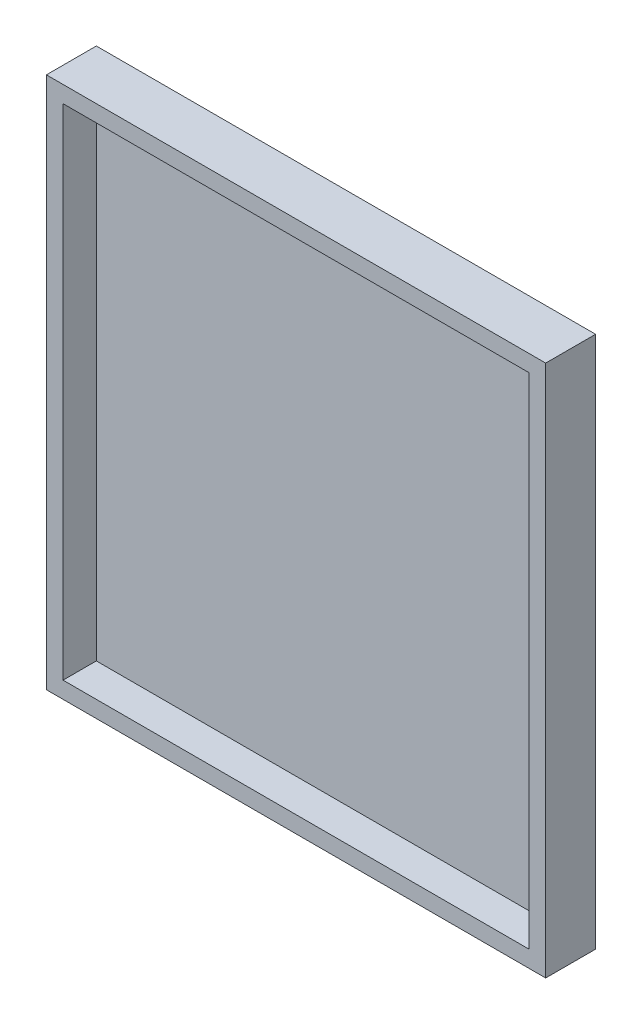
SolidWorks part; units mm, degrees
ref_plane "Front Plane" through (0, 0, 0) normal (0, 0, 1) x (1, 0, 0)
ref_plane "Top Plane" through (0, 0, 0) normal (0, 1, 0) x (1, 0, 0)
ref_plane "Right Plane" through (0, 0, 0) normal (1, 0, 0) x (0, 0, -1)
sketch "Sketch1" plane through (0, 0, 0) normal (0, 0, 1) x (1, 0, 0)
  line L1 (0, 0) -> (150, 0)
  line L2 (0, 0) -> (0, 160)
  line L3 (0, 160) -> (150, 160)
  line L4 (150, 0) -> (150, 160)
  dimension "D1" = 150
  dimension "D2" = 160
extrude "Boss-Extrude1" add sketch "Sketch1" against normal blind 5 contours L2 L3 L4 L1
sketch "Sketch2" plane through (0, 0, 0) normal (0, 0, 1) x (1, 0, 0)
  line L0 (150, 0) -> (150, 160) construction
  line L1 (0, 160) -> (150, 160)
  line L2 (0, 160) -> (0, 155)
  line L3 (0, 155) -> (150, 155)
  line L4 (150, 160) -> (150, 155)
  dimension "D1" = 5
extrude "Boss-Extrude2" add sketch "Sketch2" along normal blind 10
sketch "Sketch3" plane through (0, 0, 0) normal (0, 0, 1) x (1, 0, 0)
  line L0 (0, 155) -> (150, 155) construction
  line L1 (150, 0) -> (145, 0)
  line L2 (150, 0) -> (150, 155)
  line L3 (150, 155) -> (145, 155)
  line L4 (145, 0) -> (145, 155)
  dimension "D1" = 5
extrude "Boss-Extrude3" add sketch "Sketch3" along normal blind 10
sketch "Sketch4" plane through (0, 0, 0) normal (0, 0, 1) x (1, 0, 0)
  line L0 (145, 155) -> (145, 0) construction
  line L1 (0, 0) -> (145, 0)
  line L2 (0, 0) -> (0, 5)
  line L3 (0, 5) -> (145, 5)
  line L4 (145, 0) -> (145, 5)
  dimension "D1" = 5
extrude "Boss-Extrude4" add sketch "Sketch4" along normal blind 10
sketch "Sketch5" plane through (0, 0, 0) normal (0, 0, 1) x (1, 0, 0)
  line L0 (145, 5) -> (0, 5) construction
  line L1 (0, 155) -> (5, 155)
  line L2 (0, 155) -> (0, 5)
  line L3 (0, 5) -> (5, 5)
  line L4 (5, 155) -> (5, 5)
  dimension "D1" = 5
extrude "Boss-Extrude5" add sketch "Sketch5" along normal blind 10
